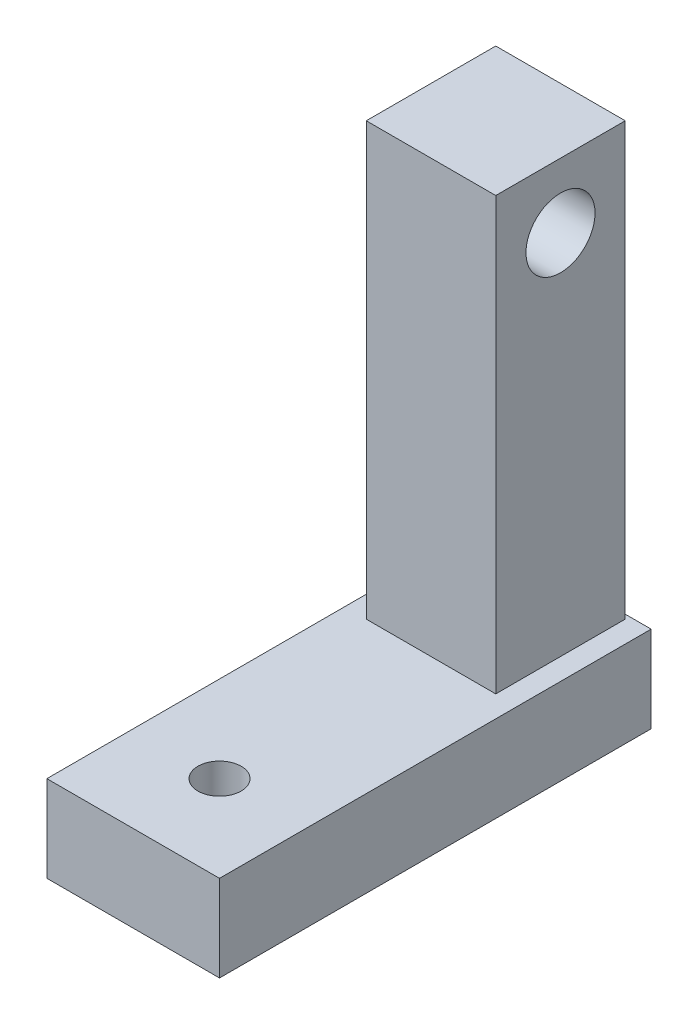
SolidWorks part; units mm, degrees
ref_plane "Plan de face" through (0, 0, 0) normal (0, 0, 1) x (1, 0, 0)
ref_plane "Plan de dessus" through (0, 0, 0) normal (0, 1, 0) x (1, 0, 0)
ref_plane "Plan de droite" through (0, 0, 0) normal (1, 0, 0) x (0, 0, -1)
sketch "Esquisse1" plane through (0, 0, 0) normal (0, 1, 0) x (1, 0, 0)
  line L0 (0, -25) -> (0, -15) construction
  line L1 (-10, 25) -> (10, 25)
  line L2 (-10, 25) -> (-10, -25)
  line L3 (-10, -25) -> (10, -25)
  line L4 (10, 25) -> (10, -25)
  line L5 (0, 15) -> (0, -15) construction
  circle A0 centre (0, -15) radius 2.5
  circle A1 centre (0, 15) radius 2.5
  dimension "D3" = 5
  dimension "D4" = 30
  dimension "D1" = 10
  dimension "D2" = 20
  dimension "D5" = 10
extrude "Boss.-Extru.1" add sketch "Esquisse1" along normal blind 10
sketch "Esquisse2" plane through (0, 10, 0) normal (0, 1, 0) x (1, 0, 0)
  line L1 (-7.5, 24.5) -> (7.5, 24.5)
  line L2 (-7.5, 24.5) -> (-7.5, 9.5)
  line L3 (-7.5, 9.5) -> (7.5, 9.5)
  line L4 (7.5, 24.5) -> (7.5, 9.5)
  point P4 (0, 9.5)
  point P5 (-7.5, 17)
  dimension "D1" = 15
  dimension "D2" = 17
extrude "Boss.-Extru.2" add sketch "Esquisse2" along normal blind 50 separate body
sketch "Esquisse3" plane through (7.5, 0, 0) normal (1, 0, 0) x (0, 0, -1)
  line L0 (17, 60) -> (17, 52.5) construction
  line L1 (9.5, 60) -> (24.5, 60) construction
  line L2 (17, 52.5) -> (9.5, 52.5) construction
  line L3 (9.5, 60) -> (9.5, 10) construction
  circle A0 centre (17, 52.5) radius 4
  dimension "D1" = 8
extrude "Enlèv. mat.-Extru.1" cut sketch "Esquisse3" against normal through all
